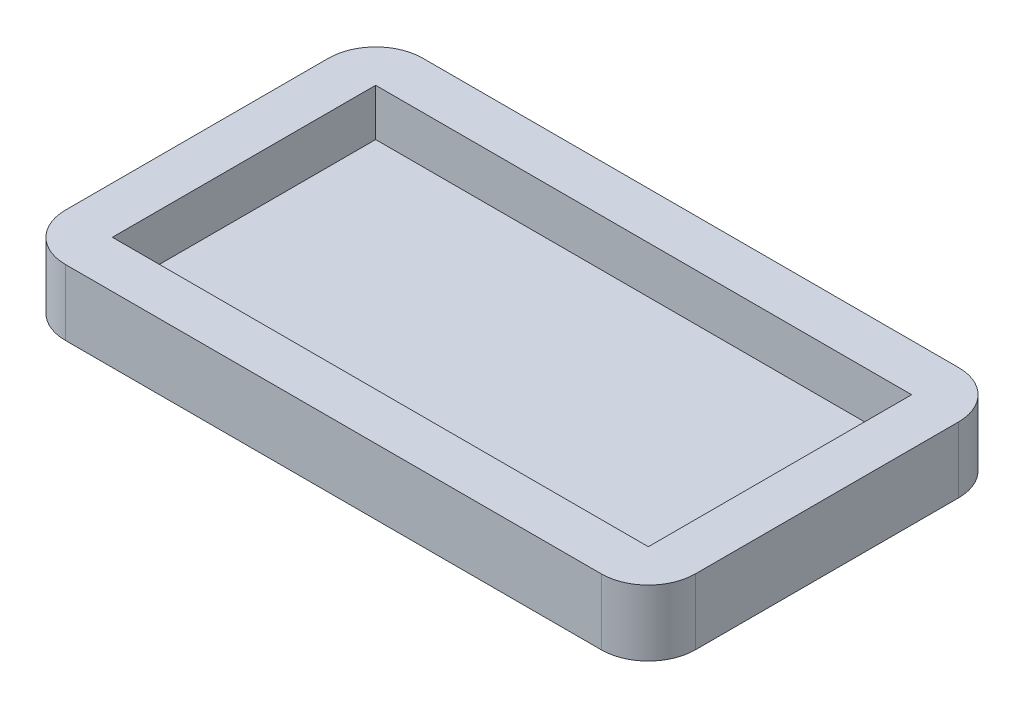
SolidWorks part; units mm, degrees
ref_plane "Front Plane" through (0, 0, 0) normal (0, 0, 1) x (1, 0, 0)
ref_plane "Top Plane" through (0, 0, 0) normal (0, 1, 0) x (1, 0, 0)
ref_plane "Right Plane" through (0, 0, 0) normal (1, 0, 0) x (0, 0, -1)
sketch "Sketch1" plane through (0, 0, 0) normal (0, 1, 0) x (1, 0, 0)
  line L0 (-43.6259, 12.3631) -> (-43.6259, -15.6369)
  line L5 (-38.6259, -20.6369) -> (18.3741, -20.6369)
  line L6 (23.3741, 12.3631) -> (23.3741, -15.6369)
  line L7 (-38.6259, 17.3631) -> (18.3741, 17.3631)
  arc A0 (23.3741, 12.3631) -> (18.3741, 17.3631) centre (18.3741, 12.3631) ccw
  arc A1 (18.3741, -20.6369) -> (23.3741, -15.6369) centre (18.3741, -15.6369) ccw
  arc A2 (-43.6259, -15.6369) -> (-38.6259, -20.6369) centre (-38.6259, -15.6369) ccw
  arc A3 (-43.6259, 12.3631) -> (-38.6259, 17.3631) centre (-38.6259, 12.3631) cw
  point P20 (0, 0)
  dimension "D4" = 5
extrude "Boss-Extrude2" add sketch "Sketch1" along normal blind 7
sketch "Sketch3" plane through (0, 7, 0) normal (0, 1, 0) x (1, 0, 0)
  line L0 (-43.6259, 12.3631) -> (-43.6259, -15.6369) construction
  line L1 (-38.6259, 12.3631) -> (18.3741, 12.3631)
  line L2 (-38.6259, 12.3631) -> (-38.6259, -15.6369)
  line L3 (-38.6259, -15.6369) -> (18.3741, -15.6369)
  line L4 (18.3741, 12.3631) -> (18.3741, -15.6369)
  line L5 (-38.6259, -20.6369) -> (18.3741, -20.6369) construction
  dimension "D1" = 57
  dimension "D2" = 28
  dimension "D3" = 5
  dimension "D4" = 5
extrude "Cut-Extrude2" cut sketch "Sketch3" against normal blind 5
